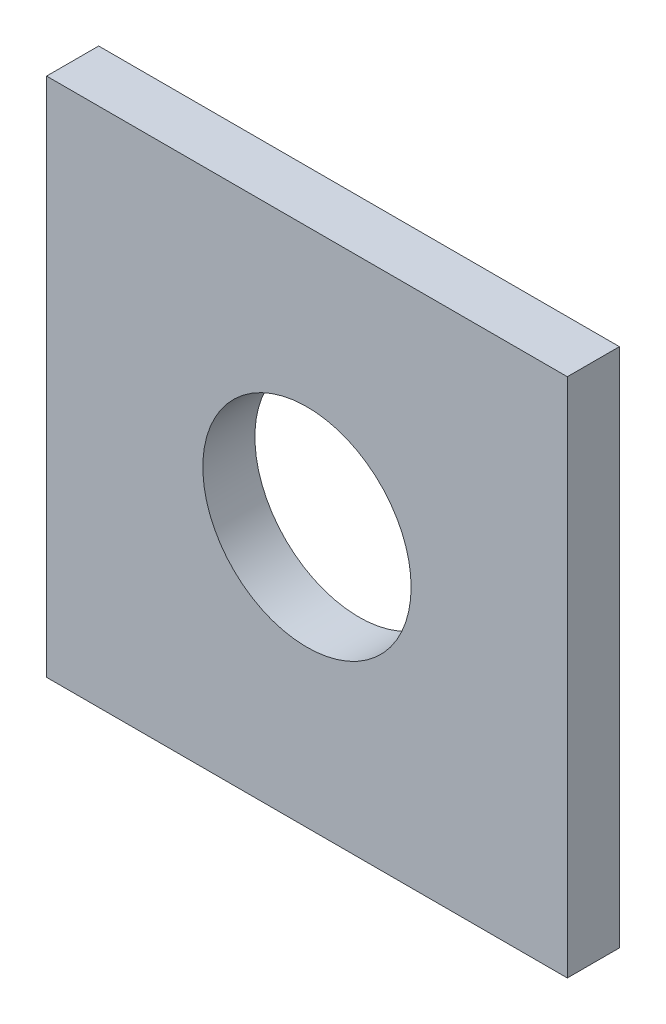
SolidWorks part; units mm, degrees
ref_plane "Alzado" through (0, 0, 0) normal (0, 0, 1) x (1, 0, 0)
ref_plane "Planta" through (0, 0, 0) normal (0, 1, 0) x (1, 0, 0)
ref_plane "Vista lateral" through (0, 0, 0) normal (1, 0, 0) x (0, 0, -1)
sketch "Croquis1" plane through (0, 0, 0) normal (0, 0, 1) x (1, 0, 0)
  line L0 (50, 50) -> (-50, -50) construction
  line L1 (-50, 50) -> (50, 50)
  line L2 (-50, 50) -> (-50, -50)
  line L3 (-50, -50) -> (50, -50)
  line L4 (50, 50) -> (50, -50)
  dimension "D1" = 100
  dimension "D2" = 100
extrude "Saliente-Extruir1" add sketch "Croquis1" along normal blind 10
sketch "Croquis2" plane through (0, 0, 10) normal (0, 0, 1) x (1, 0, 0)
  circle A0 centre (0, 0) radius 20
  dimension "D1" = 40
extrude "Cortar-Extruir1" cut sketch "Croquis2" against normal up to next
